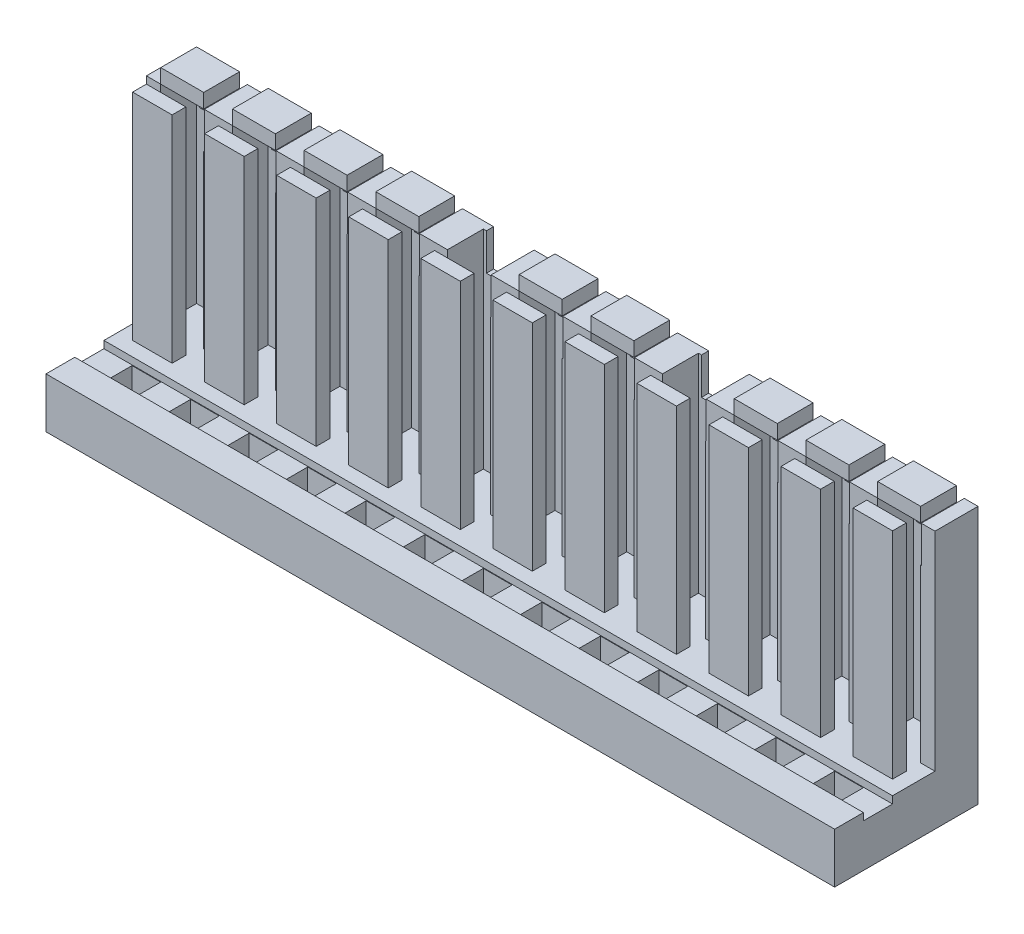
SolidWorks part; units mm, degrees
ref_plane "Front Plane" through (0, 0, 0) normal (0, 0, 1) x (1, 0, 0)
ref_plane "Top Plane" through (0, 0, 0) normal (0, 1, 0) x (1, 0, 0)
ref_plane "Right Plane" through (0, 0, 0) normal (1, 0, 0) x (0, 0, -1)
sketch "Sketch1" plane through (0, 0, 0) normal (0, 1, 0) x (1, 0, 0)
  line L1 (0, 0) -> (55, 0)
  line L2 (0, 0) -> (0, 10)
  line L3 (0, 10) -> (55, 10)
  line L4 (55, 0) -> (55, 10)
  dimension "D1" = 55
  dimension "D2" = 10
extrude "Boss-Extrude1" add sketch "Sketch1" along normal blind 18
sketch "Sketch2" plane through (0, 18, 0) normal (0, 1, 0) x (1, 0, 0)
  line L1 (55, 7) -> (0, 7)
  line L2 (55, 7) -> (55, 0)
  line L3 (55, 0) -> (0, 0)
  line L4 (0, 7) -> (0, 0)
  dimension "D1" = 7
extrude "Cut-Extrude2" cut sketch "Sketch2" against normal blind 15
sketch "Sketch3" plane through (0, 3, 0) normal (0, 1, 0) x (1, 0, 0)
  line L0 (55, 0) -> (55, 7) construction
  line L1 (53, 4) -> (51, 4)
  line L2 (53, 4) -> (53, 2)
  line L3 (53, 2) -> (51, 2)
  line L4 (51, 4) -> (51, 2)
  line L9 (0, 0) -> (55, 0) construction
  line L10 (48.9167, 4) -> (48.9167, 2)
  line L11 (48.9167, 4) -> (46.9167, 4)
  line L12 (46.9167, 4) -> (46.9167, 2)
  line L13 (48.9167, 2) -> (46.9167, 2)
  line L14 (44.8333, 4) -> (44.8333, 2)
  line L15 (44.8333, 4) -> (42.8333, 4)
  line L16 (42.8333, 4) -> (42.8333, 2)
  line L17 (44.8333, 2) -> (42.8333, 2)
  line L18 (40.75, 4) -> (40.75, 2)
  line L19 (40.75, 4) -> (38.75, 4)
  line L20 (38.75, 4) -> (38.75, 2)
  line L21 (40.75, 2) -> (38.75, 2)
  line L22 (36.6667, 4) -> (36.6667, 2)
  line L23 (36.6667, 4) -> (34.6667, 4)
  line L24 (34.6667, 4) -> (34.6667, 2)
  line L25 (36.6667, 2) -> (34.6667, 2)
  line L26 (32.5833, 4) -> (32.5833, 2)
  line L27 (32.5833, 4) -> (30.5833, 4)
  line L28 (30.5833, 4) -> (30.5833, 2)
  line L29 (32.5833, 2) -> (30.5833, 2)
  line L30 (28.5, 4) -> (28.5, 2)
  line L31 (28.5, 4) -> (26.5, 4)
  line L32 (26.5, 4) -> (26.5, 2)
  line L33 (28.5, 2) -> (26.5, 2)
  line L34 (24.4167, 4) -> (24.4167, 2)
  line L35 (24.4167, 4) -> (22.4167, 4)
  line L36 (22.4167, 4) -> (22.4167, 2)
  line L37 (24.4167, 2) -> (22.4167, 2)
  line L38 (20.3333, 4) -> (20.3333, 2)
  line L39 (20.3333, 4) -> (18.3333, 4)
  line L40 (18.3333, 4) -> (18.3333, 2)
  line L41 (20.3333, 2) -> (18.3333, 2)
  line L42 (16.25, 4) -> (16.25, 2)
  line L43 (16.25, 4) -> (14.25, 4)
  line L44 (14.25, 4) -> (14.25, 2)
  line L45 (16.25, 2) -> (14.25, 2)
  line L46 (12.1667, 4) -> (12.1667, 2)
  line L47 (12.1667, 4) -> (10.1667, 4)
  line L48 (10.1667, 4) -> (10.1667, 2)
  line L49 (12.1667, 2) -> (10.1667, 2)
  line L50 (8.0833, 4) -> (8.0833, 2)
  line L51 (8.0833, 4) -> (6.0833, 4)
  line L52 (6.0833, 4) -> (6.0833, 2)
  line L53 (8.0833, 2) -> (6.0833, 2)
  line L54 (4, 4) -> (4, 2)
  line L55 (4, 4) -> (2, 4)
  line L56 (2, 4) -> (2, 2)
  line L57 (4, 2) -> (2, 2)
  line L58 (0, 7) -> (0, 0) construction
  dimension "D1" = 2
  dimension "D2" = 2
  dimension "D3" = 2
  dimension "D4" = 2
  dimension "D6" = 2
  dimension "D5" = 13
extrude "Cut-Extrude3" cut sketch "Sketch3" against normal blind 2
sketch "Sketch4" plane through (0, 3, 0) normal (0, 1, 0) x (1, 0, 0)
  line L0 (55, 0) -> (55, 7) construction
  line L1 (55, 2.0088) -> (0, 2.0088)
  line L2 (55, 2.0088) -> (55, 0)
  line L3 (55, 0) -> (0, 0)
  line L4 (0, 2.0088) -> (0, 0)
  line L5 (0, 7) -> (0, 0) construction
extrude "Boss-Extrude2" add sketch "Sketch4" along normal blind 0.5
sketch "Sketch7" plane through (0, 3, 0) normal (0, 1, 0) x (1, 0, 0)
  line L0 (55, 2.0088) -> (55, 7) construction
  line L1 (55, 7) -> (0, 7)
  line L2 (55, 7) -> (55, 4.0401)
  line L3 (55, 4.0401) -> (0, 4.0401)
  line L4 (0, 7) -> (0, 4.0401)
extrude "Boss-Extrude3" add sketch "Sketch7" along normal blind 0.5
sketch "Sketch8" plane through (0, 0, -7) normal (0, 0, 1) x (1, 0, 0)
  line L0 (55, 3.5) -> (0, 3.5) construction
  line L1 (54, 18) -> (51, 18)
  line L2 (54, 18) -> (54, 3.5)
  line L3 (54, 3.5) -> (51, 3.5)
  line L4 (51, 18) -> (51, 3.5)
  line L5 (55, 18) -> (0, 18) construction
  line L6 (55, 3.5) -> (55, 18) construction
  line L7 (49, 18) -> (49, 3.5)
  line L8 (49, 18) -> (46, 18)
  line L9 (46, 18) -> (46, 3.5)
  line L10 (49, 3.5) -> (46, 3.5)
  line L11 (44, 18) -> (44, 3.5)
  line L12 (44, 18) -> (41, 18)
  line L13 (41, 18) -> (41, 3.5)
  line L14 (44, 3.5) -> (41, 3.5)
  line L15 (39, 18) -> (39, 3.5)
  line L16 (39, 18) -> (36, 18)
  line L17 (36, 18) -> (36, 3.5)
  line L18 (39, 3.5) -> (36, 3.5)
  line L19 (34, 18) -> (34, 3.5)
  line L20 (34, 18) -> (31, 18)
  line L21 (31, 18) -> (31, 3.5)
  line L22 (34, 3.5) -> (31, 3.5)
  line L23 (29, 18) -> (29, 3.5)
  line L24 (29, 18) -> (26, 18)
  line L25 (26, 18) -> (26, 3.5)
  line L26 (29, 3.5) -> (26, 3.5)
  line L27 (24, 18) -> (24, 3.5)
  line L28 (24, 18) -> (21, 18)
  line L29 (21, 18) -> (21, 3.5)
  line L30 (24, 3.5) -> (21, 3.5)
  line L31 (19, 18) -> (19, 3.5)
  line L32 (19, 18) -> (16, 18)
  line L33 (16, 18) -> (16, 3.5)
  line L34 (19, 3.5) -> (16, 3.5)
  line L35 (14, 18) -> (14, 3.5)
  line L36 (14, 18) -> (11, 18)
  line L37 (11, 18) -> (11, 3.5)
  line L38 (14, 3.5) -> (11, 3.5)
  line L39 (9, 18) -> (9, 3.5)
  line L40 (9, 18) -> (6, 18)
  line L41 (6, 18) -> (6, 3.5)
  line L42 (9, 3.5) -> (6, 3.5)
  line L43 (4, 18) -> (4, 3.5)
  line L44 (4, 18) -> (1, 18)
  line L45 (1, 18) -> (1, 3.5)
  line L46 (4, 3.5) -> (1, 3.5)
  line L47 (0, 3.5) -> (0, 18) construction
  dimension "D1" = 1
  dimension "D2" = 14.5
  dimension "D4" = 1
  dimension "D5" = 2
  dimension "D3" = 11
extrude "Cut-Extrude5" cut sketch "Sketch8" against normal blind 2.5
sketch "Sketch9" plane through (0, 0, -10) normal (0, 0, -1) x (-1, 0, 0)
  line L0 (-55, 18) -> (0, 18) construction
  line L1 (-51.2146, 18) -> (-54.0441, 18)
  line L2 (-51.2146, 18) -> (-51.2146, 15.4379)
  line L3 (-51.2146, 15.4379) -> (-54.0441, 15.4379)
  line L4 (-54.0441, 18) -> (-54.0441, 15.4379)
  line L5 (-46.2146, 18) -> (-46.2146, 15.4379)
  line L6 (-46.2146, 18) -> (-49.0441, 18)
  line L7 (-49.0441, 18) -> (-49.0441, 15.4379)
  line L8 (-46.2146, 15.4379) -> (-49.0441, 15.4379)
  line L9 (-41.2146, 18) -> (-41.2146, 15.4379)
  line L10 (-41.2146, 18) -> (-44.0441, 18)
  line L11 (-44.0441, 18) -> (-44.0441, 15.4379)
  line L12 (-41.2146, 15.4379) -> (-44.0441, 15.4379)
  line L13 (-36.2146, 18) -> (-36.2146, 15.4379)
  line L14 (-36.2146, 18) -> (-39.0441, 18)
  line L15 (-39.0441, 18) -> (-39.0441, 15.4379)
  line L16 (-36.2146, 15.4379) -> (-39.0441, 15.4379)
  line L17 (-31.2146, 18) -> (-31.2146, 15.4379)
  line L18 (-31.2146, 18) -> (-34.0441, 18)
  line L19 (-34.0441, 18) -> (-34.0441, 15.4379)
  line L20 (-31.2146, 15.4379) -> (-34.0441, 15.4379)
  line L21 (-26.2146, 18) -> (-26.2146, 15.4379)
  line L22 (-26.2146, 18) -> (-29.0441, 18)
  line L23 (-29.0441, 18) -> (-29.0441, 15.4379)
  line L24 (-26.2146, 15.4379) -> (-29.0441, 15.4379)
  line L25 (-21.2146, 18) -> (-21.2146, 15.4379)
  line L26 (-21.2146, 18) -> (-24.0441, 18)
  line L27 (-24.0441, 18) -> (-24.0441, 15.4379)
  line L28 (-21.2146, 15.4379) -> (-24.0441, 15.4379)
  line L29 (-16.2146, 18) -> (-16.2146, 15.4379)
  line L30 (-16.2146, 18) -> (-19.0441, 18)
  line L31 (-19.0441, 18) -> (-19.0441, 15.4379)
  line L32 (-16.2146, 15.4379) -> (-19.0441, 15.4379)
  line L33 (-11.2146, 18) -> (-11.2146, 15.4379)
  line L34 (-11.2146, 18) -> (-14.0441, 18)
  line L35 (-14.0441, 18) -> (-14.0441, 15.4379)
  line L36 (-11.2146, 15.4379) -> (-14.0441, 15.4379)
  line L37 (-6.2146, 18) -> (-6.2146, 15.4379)
  line L38 (-6.2146, 18) -> (-9.0441, 18)
  line L39 (-9.0441, 18) -> (-9.0441, 15.4379)
  line L40 (-6.2146, 15.4379) -> (-9.0441, 15.4379)
  line L41 (-1.2146, 18) -> (-1.2146, 15.4379)
  line L42 (-1.2146, 18) -> (-4.0441, 18)
  line L43 (-4.0441, 18) -> (-4.0441, 15.4379)
  line L44 (-1.2146, 15.4379) -> (-4.0441, 15.4379)
  dimension "D1" = 11
extrude "Cut-Extrude6" cut sketch "Sketch9" against normal through all
sketch "Sketch10" plane through (0, 18, 0) normal (0, 1, 0) x (1, 0, 0)
  line L0 (49, 9.5) -> (49, 7)
  line L1 (54, 9.5) -> (51, 9.5)
  line L2 (54, 9.5) -> (54, 7)
  line L3 (54, 7) -> (51, 7)
  line L4 (51, 9.5) -> (51, 7)
  line L5 (49, 9.5) -> (46, 9.5)
  line L6 (46, 9.5) -> (46, 7)
  line L7 (49, 7) -> (46, 7)
  line L8 (44, 9.5) -> (44, 7)
  line L9 (44, 9.5) -> (41, 9.5)
  line L10 (41, 9.5) -> (41, 7)
  line L11 (44, 7) -> (41, 7)
  line L16 (34, 9.5) -> (34, 7)
  line L17 (34, 9.5) -> (31, 9.5)
  line L18 (31, 9.5) -> (31, 7)
  line L19 (34, 7) -> (31, 7)
  line L20 (29, 9.5) -> (29, 7)
  line L21 (29, 9.5) -> (26, 9.5)
  line L22 (26, 9.5) -> (26, 7)
  line L23 (29, 7) -> (26, 7)
  line L28 (19, 9.5) -> (19, 7)
  line L29 (19, 9.5) -> (16, 9.5)
  line L30 (16, 9.5) -> (16, 7)
  line L31 (19, 7) -> (16, 7)
  line L32 (14, 9.5) -> (14, 7)
  line L33 (14, 9.5) -> (11, 9.5)
  line L34 (11, 9.5) -> (11, 7)
  line L35 (14, 7) -> (11, 7)
  line L36 (9, 9.5) -> (9, 7)
  line L37 (9, 9.5) -> (6, 9.5)
  line L38 (6, 9.5) -> (6, 7)
  line L39 (9, 7) -> (6, 7)
  line L40 (4, 9.5) -> (4, 7)
  line L41 (4, 9.5) -> (1, 9.5)
  line L42 (1, 9.5) -> (1, 7)
  line L43 (4, 7) -> (1, 7)
  line L44 (0, 10) -> (0, 7) construction
  line L45 (39, 9.5) -> (39, 7) [skipped]
  line L46 (39, 7) -> (36, 7) [skipped]
  line L47 (36, 9.5) -> (36, 7) [skipped]
  line L48 (39, 9.5) -> (36, 9.5) [skipped]
  line L49 (24, 9.5) -> (24, 7) [skipped]
  line L50 (24, 7) -> (21, 7) [skipped]
  line L51 (21, 9.5) -> (21, 7) [skipped]
  line L52 (24, 9.5) -> (21, 9.5) [skipped]
  dimension "D2" = 1
  dimension "D1" = 11
extrude "Boss-Extrude4" add sketch "Sketch10" along normal blind 1 separate body
sketch "Sketch11" plane through (0, 3.5, 0) normal (0, 1, 0) x (1, 0, 0)
  line L0 (0, 4.0401) -> (55, 4.0401) construction
  line L1 (54, 6) -> (51.2452, 6)
  line L2 (54, 6) -> (54, 5.0401)
  line L3 (54, 5.0401) -> (51.2452, 5.0401)
  line L4 (51.2452, 6) -> (51.2452, 5.0401)
  line L5 (55, 7) -> (54, 7) construction
  line L6 (55, 4.0401) -> (55, 7) construction
  line L7 (48.9755, 6) -> (48.9755, 5.0401)
  line L8 (48.9755, 6) -> (46.2206, 6)
  line L9 (46.2206, 6) -> (46.2206, 5.0401)
  line L10 (48.9755, 5.0401) -> (46.2206, 5.0401)
  line L11 (43.951, 6) -> (43.951, 5.0401)
  line L12 (43.951, 6) -> (41.1961, 6)
  line L13 (41.1961, 6) -> (41.1961, 5.0401)
  line L14 (43.951, 5.0401) -> (41.1961, 5.0401)
  line L15 (38.9265, 6) -> (38.9265, 5.0401)
  line L16 (38.9265, 6) -> (36.1716, 6)
  line L17 (36.1716, 6) -> (36.1716, 5.0401)
  line L18 (38.9265, 5.0401) -> (36.1716, 5.0401)
  line L19 (33.9019, 6) -> (33.9019, 5.0401)
  line L20 (33.9019, 6) -> (31.1471, 6)
  line L21 (31.1471, 6) -> (31.1471, 5.0401)
  line L22 (33.9019, 5.0401) -> (31.1471, 5.0401)
  line L23 (28.8774, 6) -> (28.8774, 5.0401)
  line L24 (28.8774, 6) -> (26.1226, 6)
  line L25 (26.1226, 6) -> (26.1226, 5.0401)
  line L26 (28.8774, 5.0401) -> (26.1226, 5.0401)
  line L27 (23.8529, 6) -> (23.8529, 5.0401)
  line L28 (23.8529, 6) -> (21.0981, 6)
  line L29 (21.0981, 6) -> (21.0981, 5.0401)
  line L30 (23.8529, 5.0401) -> (21.0981, 5.0401)
  line L31 (18.8284, 6) -> (18.8284, 5.0401)
  line L32 (18.8284, 6) -> (16.0735, 6)
  line L33 (16.0735, 6) -> (16.0735, 5.0401)
  line L34 (18.8284, 5.0401) -> (16.0735, 5.0401)
  line L35 (13.8039, 6) -> (13.8039, 5.0401)
  line L36 (13.8039, 6) -> (11.049, 6)
  line L37 (11.049, 6) -> (11.049, 5.0401)
  line L38 (13.8039, 5.0401) -> (11.049, 5.0401)
  line L39 (8.7794, 6) -> (8.7794, 5.0401)
  line L40 (8.7794, 6) -> (6.0245, 6)
  line L41 (6.0245, 6) -> (6.0245, 5.0401)
  line L42 (8.7794, 5.0401) -> (6.0245, 5.0401)
  line L43 (3.7548, 6) -> (3.7548, 5.0401)
  line L44 (3.7548, 6) -> (1, 6)
  line L45 (1, 6) -> (1, 5.0401)
  line L46 (3.7548, 5.0401) -> (1, 5.0401)
  line L47 (0, 7) -> (0, 4.0401) construction
  dimension "D1" = 1
  dimension "D2" = 1
  dimension "D3" = 0.9599
  dimension "D5" = 0.2452
  dimension "D7" = 1
  dimension "D6" = 11
extrude "Boss-Extrude5" add sketch "Sketch11" along normal blind 15
